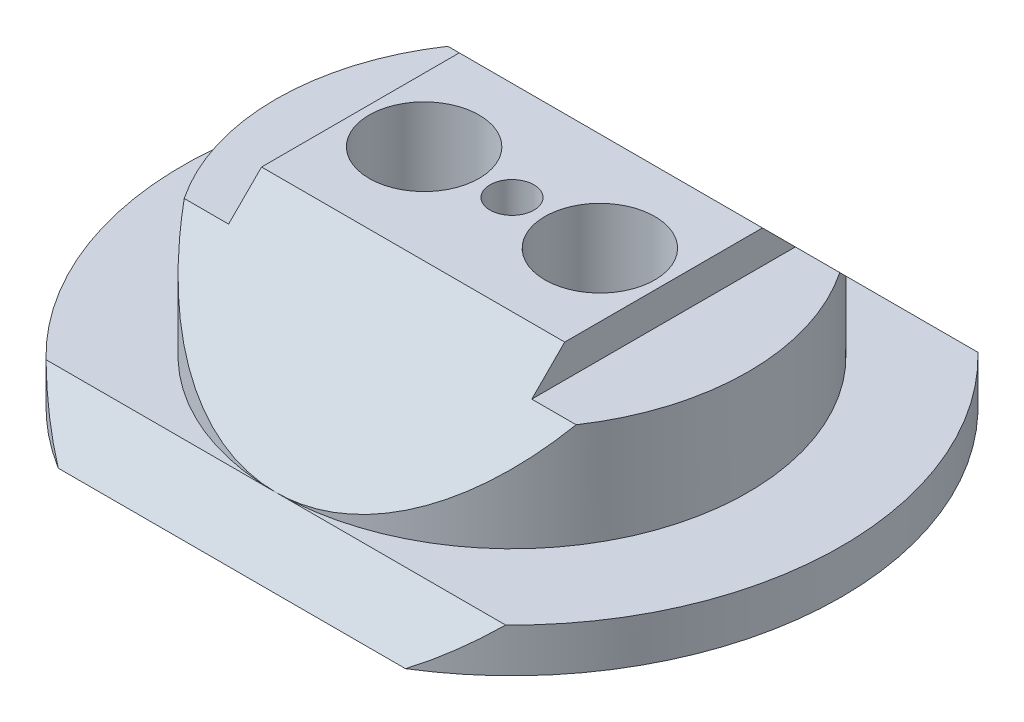
SolidWorks part; units mm, degrees
ref_plane "Front Plane" through (0, 0, 0) normal (0, 0, 1) x (1, 0, 0)
ref_plane "Top Plane" through (0, 0, 0) normal (0, 1, 0) x (1, 0, 0)
ref_plane "Right Plane" through (0, 0, 0) normal (1, 0, 0) x (0, 0, -1)
sketch "Sketch1" plane through (0, 0, 0) normal (0, 1, 0) x (1, 0, 0)
  circle A0 centre (0, 0) radius 30
extrude "Boss-Extrude1" add sketch "Sketch1" along normal blind 4
sketch "Sketch2" plane through (0, 0, 0) normal (1, 0, 0) x (0, 0, -1)
  line L0 (0, 4) -> (21.5, 4)
  line L1 (30, 4) -> (-30, 4) construction
  line L3 (0, 4) -> (-21.5, 4)
  line L5 (0, 4) -> (0, 19.5) construction
  line L6 (-9, 16.5) -> (-21.5, 4)
  line L7 (-9, 16.5) -> (9, 16.5)
  line L9 (9, 16.5) -> (21.5, 4)
  dimension "D1" = 12.5
  dimension "D2" = 45
  dimension "D3" = 21.5
  dimension "D4" = 21.5
  dimension "D5" = 45
sketch "Sketch3" plane through (0, 4, 0) normal (0, 1, 0) x (1, 0, 0)
  circle A0 centre (0, 0) radius 21.5
  dimension "D1" = 43
extrude "Boss-Extrude2" add sketch "Sketch2" along normal up to surface and the other way up to surface up to face at (0, 4, 30) other way up to face at (0, 4, 30)
ref_plane "Plane1" through (0, 12.75, -12.75) normal (0, 0.7071, -0.7071) x (1, 0, 0)
other "SurfaceCut1"
ref_plane "Plane2" through (0, 12.75, 12.75) normal (0, 0.7071, 0.7071) x (1, 0, 0)
other "SurfaceCut2"
extrude "Cut-Extrude2" cut sketch "Sketch3" against normal up to surface (12.5 mm away) flip side to cut contours A0
sketch "Sketch5" plane through (0, 0, 0) normal (0, -1, 0) x (-1, 0, 0)
  line L0 (0, 0) -> (0, -6)
  line L1 (0, -6) -> (-17.5, -6)
  line L2 (-17.5, -6) -> (-17.5, 6)
  line L3 (-17.5, 6) -> (17.5, 6)
  line L4 (17.5, 6) -> (17.5, -6)
  line L5 (17.5, -6) -> (0, -6)
  circle A0 centre (0, 0) radius 6
  circle A1 centre (0, 0) radius 3.5
  dimension "D1" = 12
  dimension "D2" = 7
  dimension "D3" = 12
  dimension "D4" = 6
  dimension "D5" = 35
  dimension "D6" = 17.5
extrude "Boss-Extrude3" add sketch "Sketch5" along normal blind 18 contours L1 L2 L3 L4 L5
sketch "Sketch6" plane through (0, 0, 0) normal (0, -1, 0) x (1, 0, 0)
  line L0 (0, 6) -> (0, 15) construction
  line L1 (-17.5, 6) -> (17.5, 6) construction
  line L2 (0, 15) -> (7, 15)
  line L3 (7, 15) -> (7, 6)
  line L4 (-17.5, 6) -> (17.5, 6) construction
  line L5 (7, 6) -> (-7, 6)
  line L6 (-7, 6) -> (-7, 15)
  line L7 (-7, 15) -> (0, 15)
  dimension "D1" = 14
  dimension "D2" = 9
extrude "Boss-Extrude4" add sketch "Sketch6" along normal blind 15 contours L7 L2 L3 L5 L6
sketch "Sketch7" plane through (0, 0, 0) normal (0, -1, 0) x (1, 0, 0)
  line L0 (0, -6) -> (0, -15) construction
  line L1 (17.5, -6) -> (-17.5, -6) construction
  line L2 (0, -15) -> (7, -15)
  line L3 (7, -15) -> (7, -6)
  line L4 (7, -6) -> (-7, -6)
  line L7 (-7, -6) -> (-7, -15)
  line L8 (-7, -15) -> (0, -15)
  dimension "D1" = 9
  dimension "D2" = 14
extrude "Boss-Extrude5" add sketch "Sketch7" along normal blind 15
sketch "Sketch8" plane through (0, 0, 0) normal (0, 0, 1) x (1, 0, 0)
  line L0 (0, 0) -> (12.5, 0) construction
  line L1 (12.5, 0) -> (12.5, -12.5) construction
  line L2 (12.5, -12.5) -> (-12.5, -12.5) construction
  line L3 (-12.5, -12.5) -> (-12.5, 0) construction
  line L4 (-12.5, 0) -> (0, 0) construction
  circle A0 centre (-12.5, -12.5) radius 2
  circle A1 centre (12.5, -12.5) radius 2
  dimension "D4" = 4
  dimension "D5" = 4
  dimension "D1" = 12.5
  dimension "D2" = 25
  dimension "D3" = 12.5
extrude "Cut-Extrude3" cut sketch "Sketch8" against normal through all both and the other way through all contours A0 | A1
ref_plane "Plane3" through (0, -18, 0) normal (0, -1, 0) x (-1, 0, 0)
ref_plane "Plane4" through (10.366, -9.6749, -8.0624) normal (0.6355, -0.5931, -0.4943) x (-0.3613, 0.3373, -0.8693)
ref_plane "Plane5" through (-10.366, -9.6749, -8.0624) normal (0.6355, 0.5931, 0.4943) x (0.3613, 0.3373, -0.8693)
ref_plane "Plane6" through (10.366, -9.6749, 8.0624) normal (-0.6355, 0.5931, -0.4943) x (-0.3613, 0.3373, 0.8693)
ref_plane "Plane7" through (-10.366, -9.6749, 8.0624) normal (0.6355, 0.5931, -0.4943) x (-0.3613, -0.3373, -0.8693)
ref_plane "Plane9" through (0, 0, 6) normal (0, 0, 1) x (1, 0, 0)
sketch "Sketch16" plane through (0, 0, 6) normal (0, 0, 1) x (1, 0, 0)
  line L0 (17.5, -18) -> (17.5, -14.5)
  line L1 (-6.6, -18) -> (6.6, -18) construction
  line L2 (17.5, -18) -> (17.5, 0) construction
  line L3 (17.5, -18) -> (14, -18)
  line L4 (17.5, -14.5) -> (14, -18)
  line L5 (-17.5, -18) -> (-14, -18)
  line L6 (-17.5, -18) -> (-17.5, 0) construction
  line L7 (-14, -18) -> (-17.5, -14.5)
  line L8 (-17.5, -14.5) -> (-17.5, -18)
  dimension "D2" = 3.5
extrude "Cut-Extrude8" cut sketch "Sketch16" against normal through all both and the other way through all
sketch "Sketch17" plane through (10.366, -9.6749, -8.0624) normal (0.6355, -0.5931, -0.4943) x (-0.3613, 0.3373, -0.8693)
  line L0 (-2.3725, -6.1896) -> (7.9806, -0.7067)
  line L1 (5.4512, -6.1896) -> (10.5101, 4.7762) construction
  line L2 (7.9806, -0.7067) -> (7.9806, -10.9658)
  line L3 (10.5101, -15.7421) -> (5.4512, -6.1896) construction
  line L4 (7.9806, -10.9658) -> (-2.3725, -6.1896)
extrude "Cut-Extrude9" cut sketch "Sketch17" along normal through all
sketch "Sketch19" plane through (-10.366, -9.6749, -8.0624) normal (0.6355, 0.5931, 0.4943) x (0.3613, 0.3373, -0.8693)
  line L0 (-2.3725, -6.1896) -> (7.9806, -10.9658)
  line L1 (7.9806, -10.9658) -> (7.9806, -0.7067)
  line L2 (5.4512, -6.1896) -> (10.5101, 4.7762) construction
  line L3 (7.9806, -0.7067) -> (-2.3725, -6.1896)
extrude "Cut-Extrude11" cut sketch "Sketch19" against normal blind 20 contours L3 L0 L1
sketch "Sketch20" plane through (-10.366, -9.6749, 8.0624) normal (0.6355, 0.5931, -0.4943) x (-0.3613, -0.3373, -0.8693)
  line L0 (2.3725, -6.1896) -> (-7.9806, -0.7067)
  line L1 (-5.4512, -6.1896) -> (-10.5101, 4.7762) construction
  line L2 (-7.9806, -0.7067) -> (-7.9806, -10.9658)
  line L3 (-5.4512, -6.1896) -> (-10.5101, -15.7421) construction
  line L4 (-7.9806, -10.9658) -> (2.3725, -6.1896)
extrude "Cut-Extrude12" cut sketch "Sketch20" against normal blind 20
sketch "Sketch21" plane through (10.366, -9.6749, 8.0624) normal (-0.6355, 0.5931, -0.4943) x (-0.3613, 0.3373, 0.8693)
  line L0 (-2.3725, -6.1896) -> (7.9806, -0.7067)
  line L1 (5.4512, -6.1896) -> (10.5101, 4.7762) construction
  line L2 (7.9806, -0.7067) -> (7.9806, -10.9658)
  line L3 (7.9806, -10.9658) -> (-2.3725, -6.1896)
extrude "Cut-Extrude13" cut sketch "Sketch21" against normal blind 20 contours L0 L2 L3
ref_plane "Plane10" through (0, 16.5, 0) normal (0, 1, 0) x (1, 0, 0)
sketch "Sketch25" plane through (0, 0, 0) normal (0, 0, 1) x (1, 0, 0)
  line L1 (-33.0377, 0) -> (33.0377, 0)
  line L2 (-33.0377, 0) -> (-33.0377, -20.1422)
  line L3 (-33.0377, -20.1422) -> (33.0377, -20.1422)
  line L4 (33.0377, 0) -> (33.0377, -20.1422)
  dimension "D1" = 20.1422
  dimension "D2" = 66.0754
extrude "Cut-Extrude14" cut sketch "Sketch25" along normal through all both and the other way through all
sketch "Sketch26" plane through (0, 16.5, 0) normal (0, 1, 0) x (1, 0, 0)
  line L0 (-9.075, 0) -> (9.075, 0) construction
  circle A0 centre (-8, 0) radius 5.005
  circle A2 centre (8, 0) radius 5.005
  dimension "D1" = 10.01
  dimension "D2" = 10.01
  dimension "D3" = 8
  dimension "D4" = 8
extrude "Cut-Extrude15" cut sketch "Sketch26" against normal blind 24
sketch "Sketch29" plane through (0, 0, 6) normal (0, 0, 1) x (1, 0, 0)
  line L0 (21.5, 4) -> (21.5, 16.5) construction
  line L1 (21.5, 13.5) -> (13.8, 13.5)
  line L2 (21.5, 13.5) -> (21.5, 16.5)
  line L3 (21.5, 16.5) -> (13.8, 16.5)
  line L4 (13.8, 13.5) -> (13.8, 16.5)
  line L5 (9.9, 16.5) -> (-9.9, 16.5) construction
  dimension "D1" = 3
  dimension "D2" = 7.7
extrude "Cut-Extrude17" cut sketch "Sketch29" against normal through all both and the other way through all
sketch "Sketch31" plane through (0, 0, 6) normal (0, 0, 1) x (1, 0, 0)
  line L0 (-21.5, 16.5) -> (-21.5, 4) construction
  line L1 (-21.5, 13.5) -> (-13.8, 13.5)
  line L2 (-21.5, 13.5) -> (-21.5, 16.5)
  line L3 (-21.5, 16.5) -> (-13.8, 16.5)
  line L4 (-13.8, 13.5) -> (-13.8, 16.5)
  line L5 (9.9, 16.5) -> (-9.9, 16.5) construction
  dimension "D1" = 3
  dimension "D2" = 7.7
extrude "Cut-Extrude18" cut sketch "Sketch31" against normal through all both and the other way through all
sketch "Sketch34" plane through (0, 0, 0) normal (0, -1, 0) x (1, 0, 0)
  circle A0 centre (0, 0) radius 1.5
  dimension "D1" = 3
extrude "Cut-Extrude21" cut sketch "Sketch34" against normal blind 20
sketch "Sketch35" plane through (0, 16.5, 0) normal (0, 1, 0) x (1, 0, 0)
  circle A0 centre (0, 0) radius 2
  dimension "D1" = 4
extrude "Cut-Extrude22" cut sketch "Sketch35" against normal blind 3
sketch "Sketch37" plane through (0, 0, 0) normal (0, -1, 0) x (1, 0, 0)
  line L0 (0, -9.075) -> (0, 9.075) construction
  line L1 (9.075, 0) -> (-9.075, 0) construction
  circle A0 centre (0, -15) radius 5
  circle A1 centre (0, 15) radius 5
  circle A2 centre (-22, 0) radius 5
  circle A3 centre (22, 0) radius 5
  circle A4 centre (-14, 12) radius 5
  circle A5 centre (14, 12) radius 5
  circle A6 centre (-14, -12) radius 5
  circle A7 centre (14, -12) radius 5
  dimension "D1" = 10
  dimension "D2" = 10
  dimension "D3" = 10
  dimension "D4" = 10
  dimension "D10" = 10
  dimension "D14" = 10
  dimension "D15" = 10
  dimension "D16" = 10
  dimension "D5" = 15
  dimension "D6" = 15
  dimension "D7" = 22
  dimension "D8" = 22
  dimension "D9" = 14
  dimension "D11" = 12
  dimension "D12" = 12
  dimension "D13" = 14
  dimension "D17" = 12
  dimension "D18" = 14
  dimension "D19" = 14
  dimension "D20" = 12
extrude "Cut-Extrude23" cut sketch "Sketch37" against normal blind 3
